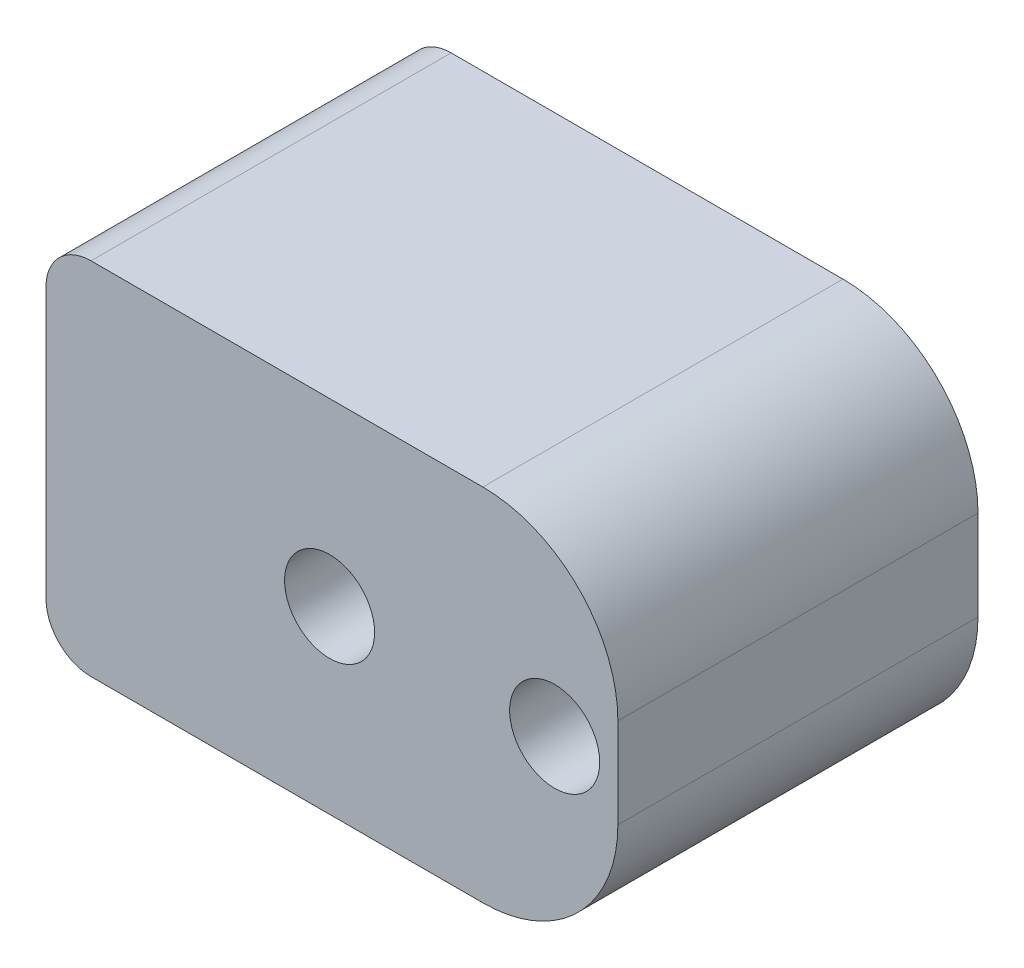
SolidWorks part; units mm, degrees
ref_plane "Front" through (0, 0, 0) normal (0, 0, 1) x (1, 0, 0)
ref_plane "Top" through (0, 0, 0) normal (0, 1, 0) x (1, 0, 0)
ref_plane "Right" through (0, 0, 0) normal (1, 0, 0) x (0, 0, -1)
sketch "Sketch1" plane through (0, 0, 0) normal (0, 0, 1) x (1, 0, 0)
  line L0 (-6.3, 4) -> (0, 4)
  line L1 (0, -4) -> (-6.3, -4)
  line L2 (-6.3, 4) -> (-6.3, -4)
  line L3 (55, 0) -> (-55, 0) construction
  line L4 (0, 4) -> (6.4045, 4)
  line L5 (0, 4) -> (0, -4)
  line L6 (0, -4) -> (6.4045, -4)
  line L7 (6.4045, 4) -> (6.4045, -4)
  circle A0 centre (0, 0) radius 4
  circle A1 centre (0, 0) radius 1
  circle A2 centre (5, 0) radius 1
  dimension "D1" = 8
  dimension "D3" = 2
  dimension "D4" = 5
  dimension "D2" = 6.3
extrude "Boss-Extrude1" add sketch "Sketch1" along normal blind 8 contours A0 L0 L2 L1 | A1 L5 A0 | A1 L5 A0 | A0 A2 L6 L7 L4
sketch "Sketch4" plane through (-6.3, 0, 0) normal (-1, 0, 0) x (0, 0, 1)
  line L0 (55, 0) -> (-55, 0) construction
  circle A0 centre (4, 0) radius 3.25
  dimension "D1" = 6.5
extrude "Cut-Extrude3" cut sketch "Sketch4" against normal blind 2.7 from offset 0.8 offset against normal yes
ref_plane "Plane1" through (0, 0, 4) normal (0, 0, 1) x (1, 0, 0)
sketch "Sketch3" plane through (0, 0, 4) normal (0, 0, 1) x (1, 0, 0)
  line L0 (55, 0) -> (-55, 0) construction
  circle A0 centre (-5, 0) radius 3.25
  circle A1 centre (0, 0) radius 1 construction
  dimension "D1" = 6.5
  dimension "D2" = 5
extrude "Cut-Extrude2" [suppressed] cut sketch "Sketch3" against normal mid plane 2.3
fillet "Fillet2" radius 1 2 edges at (-6.3, -4, 4) (-6.3, 4, 4)
fillet "Fillet3" radius 3 2 edges at (6.4045, -4, 4) (6.4045, 4, 4)
